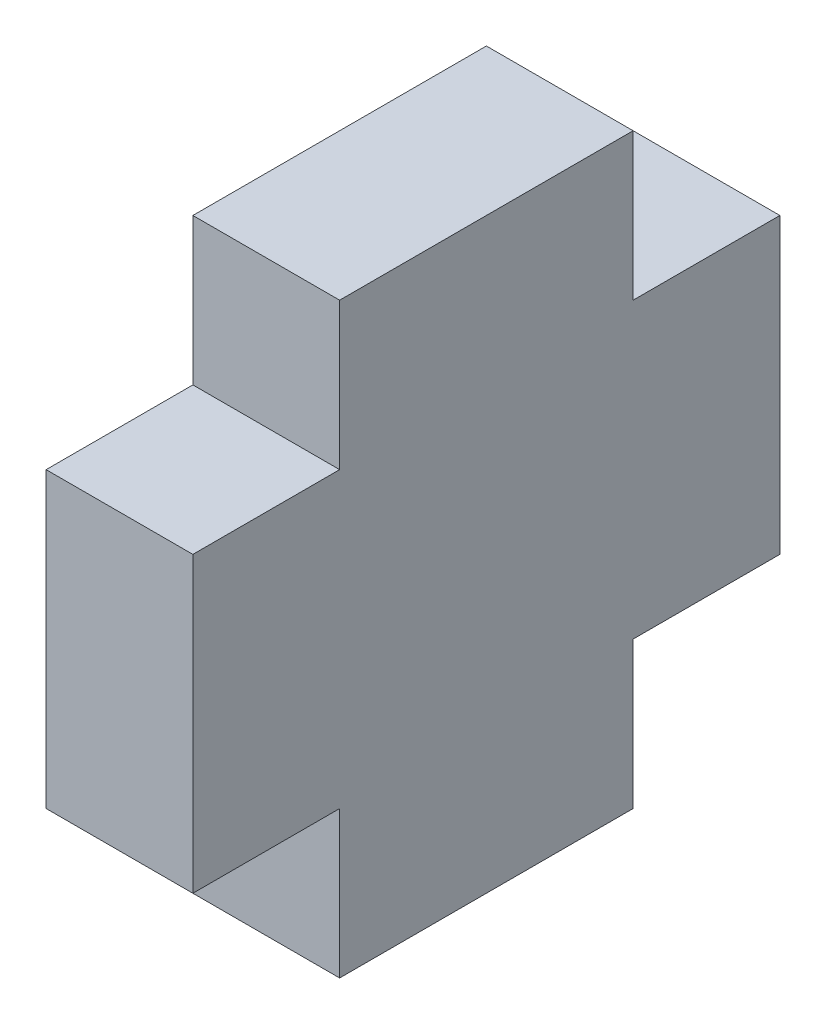
SolidWorks part; units mm, degrees
ref_plane "Front Plane" through (0, 0, 0) normal (0, 0, 1) x (1, 0, 0)
ref_plane "Top Plane" through (0, 0, 0) normal (0, 1, 0) x (1, 0, 0)
ref_plane "Right Plane" through (0, 0, 0) normal (1, 0, 0) x (0, 0, -1)
sketch "Sketch1" plane through (0, 0, 0) normal (1, 0, 0) x (0, 0, -1)
  line L0 (-70.0741, 0) -> (70.963, 0) construction
  line L1 (0, 50.4444) -> (0, -50.1481) construction
  line L2 (10, 20) -> (-10, 20)
  line L3 (-10, 20) -> (-10, 10)
  line L4 (-10, 10) -> (-20, 10)
  line L5 (-20, 10) -> (-20, -10)
  line L6 (70.0741, 0) -> (-70.963, 0) construction
  line L7 (20, 10) -> (20, -10)
  line L8 (10, 10) -> (20, 10)
  line L9 (10, 20) -> (10, 10)
  line L10 (0, -50.4444) -> (0, 50.1481) construction
  line L11 (10, -20) -> (10, -10)
  line L12 (10, -10) -> (20, -10)
  line L13 (-10, -10) -> (-20, -10)
  line L14 (-10, -20) -> (-10, -10)
  line L15 (10, -20) -> (-10, -20)
  point P16 (0, 20)
  point P21 (20, 0)
  point P22 (-20, 0)
  point P24 (0, -20)
  dimension "D1" = 10
  dimension "D2" = 10
  dimension "D3" = 10
  dimension "D4" = 10
extrude "Boss-Extrude1" add sketch "Sketch1" along normal blind 10
